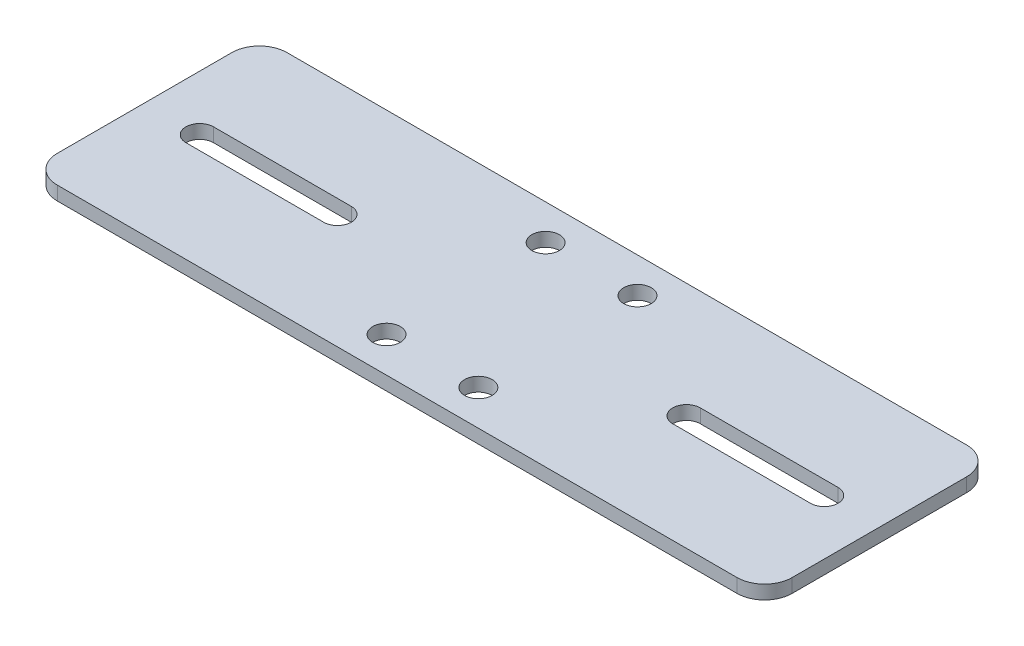
SolidWorks part; units mm, degrees
material "Thornel Mat VMA"
ref_plane "Front Plane" through (0, 0, 0) normal (0, 0, 1) x (1, 0, 0)
ref_plane "Top Plane" through (0, 0, 0) normal (0, 1, 0) x (1, 0, 0)
ref_plane "Right Plane" through (0, 0, 0) normal (1, 0, 0) x (0, 0, -1)
sketch "Sketch2" plane through (0, 0, 0) normal (0, 1, 0) x (1, 0, 0)
  line L0 (-40, 0) -> (40, 0) construction
  line L1 (-40, -12.5) -> (40, -12.5)
  line L2 (-40, -12.5) -> (-40, 12.5)
  line L3 (-40, 12.5) -> (40, 12.5)
  line L4 (40, -12.5) -> (40, 12.5)
  line L5 (-40, -12.5) -> (40, 12.5) construction
  line L6 (-40, 12.5) -> (40, -12.5) construction
  line L7 (34, 0) -> (19, 0) construction
  line L8 (34, -1.5) -> (19, -1.5)
  line L9 (34, 1.5) -> (19, 1.5)
  line L10 (0, 12.5) -> (0, -12.5) construction
  line L11 (-34, 0) -> (-19, 0) construction
  line L12 (-34, -1.5) -> (-19, -1.5)
  line L13 (-34, 1.5) -> (-19, 1.5)
  line L15 (0, 0) -> (6.1235, -6.1235) construction
  arc A0 (34, -1.5) -> (34, 1.5) centre (34, 0) ccw
  arc A1 (19, 1.5) -> (19, -1.5) centre (19, 0) ccw
  arc A2 (-34, -1.5) -> (-34, 1.5) centre (-34, 0) cw
  arc A3 (-19, 1.5) -> (-19, -1.5) centre (-19, 0) cw
  circle A4 centre (0, 0) radius 10 construction
  circle A6 centre (5, -8.6603) radius 1.5
  circle A7 centre (-5, -8.6603) radius 1.5
  circle A9 centre (-5, 8.6603) radius 1.5
  circle A10 centre (5, 8.6603) radius 1.5
  point P0 (0, 0)
  point P10 (26.5, 0)
  point P19 (-26.5, 0)
  point P37 (0, 0)
  point P40 (0, 0)
  point P45 (0, 0)
  dimension "D6" = 20
  dimension "D1" = 80
  dimension "D2" = 25
  dimension "D3" = 3
  dimension "D4" = 6
  dimension "D5" = 15
extrude "Boss-Extrude1" add sketch "Sketch2" against normal blind 1.5
fillet "Fillet2" radius 3 4 edges at (40, -0.75, 12.5) (40, -0.75, -12.5) (-40, -0.75, -12.5) (-40, -0.75, 12.5)
